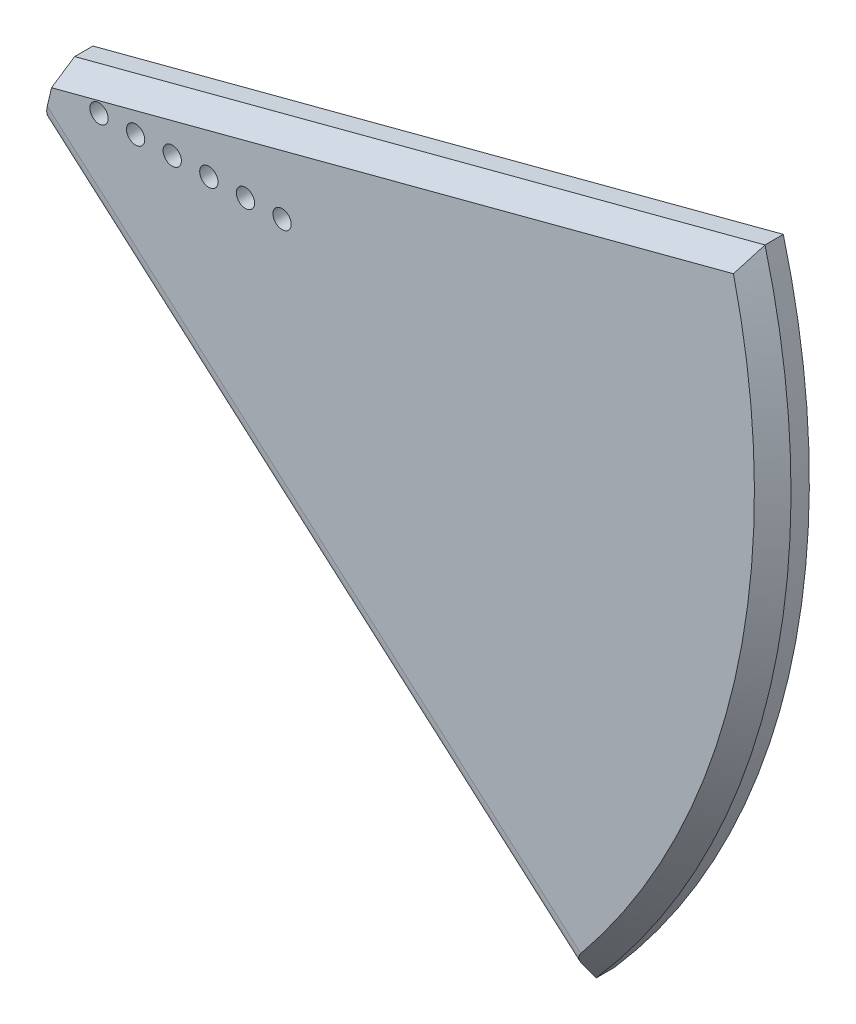
SolidWorks part; units mm, degrees
ref_plane "Front Plane" through (0, 0, 0) normal (0, 0, 1) x (1, 0, 0)
ref_plane "Top Plane" through (0, 0, 0) normal (0, 1, 0) x (1, 0, 0)
ref_plane "Right Plane" through (0, 0, 0) normal (1, 0, 0) x (0, 0, -1)
sketch "Sketch1" plane through (0, 0, 0) normal (0, 0, 1) x (1, 0, 0)
  line L0 (0, 0) -> (6.2, 0) construction
  line L2 (3.0097, -2.6348) -> (32.3538, -28.3237) construction
  line L11 (6.2, 0) -> (8.2, 0) construction
  line L12 (8.2, 0) -> (10.2, 0) construction
  line L15 (10.2, 0) -> (12.2, 0) construction
  line L16 (12.2, 0) -> (14.2, 0) construction
  line L17 (14.2, 0) -> (16.2, 0) construction
  line L18 (6.2, 0) -> (8.2, 0) construction
  line L20 (8.2, 0) -> (10.2, 0) construction
  line L21 (10.2, 0) -> (12.2, 0) construction
  line L22 (12.2, 0) -> (14.2, 0) construction
  line L23 (14.2, 0) -> (16.2, 0) construction
  line L24 (16.2, 0) -> (35, 0) construction
  line L27 (0, 0) -> (26.3345, -23.0542) construction
  line L28 (0, 0) -> (33.8429, 8.9253) construction
  line L29 (3.8678, 1.02) -> (41.5784, 10.9654) construction
  line L36 (3.8678, 1.02) -> (41.5784, 10.9654)
  line L37 (3.0097, -2.6348) -> (32.3538, -28.3237)
  line L38 (3.0097, -2.6348) -> (3.8678, 1.02)
  circle A1 centre (35, 0) radius 7 construction
  circle A6 centre (0, 0) radius 35 construction
  circle A8 centre (0, 0) radius 43 construction
  circle A9 centre (31.3429, -15.5764) radius 7 construction
  circle A24 centre (6.2, 0) radius 0.5
  circle A25 centre (8.2, 0) radius 0.5
  circle A26 centre (10.2, 0) radius 0.5
  circle A27 centre (12.2, 0) radius 0.5
  circle A28 centre (14.2, 0) radius 0.5
  circle A29 centre (16.2, 0) radius 0.5
  circle A31 centre (0, 0) radius 4 construction
  arc A32 (3.0097, -2.6348) -> (3.8678, 1.02) centre (0, 0) ccw construction
  arc A33 (32.3538, -28.3237) -> (41.5784, 10.9654) centre (0, 0) ccw construction
  arc A34 (41.5784, 10.9654) -> (32.3538, -28.3237) centre (0, 0) cw
  point P1 (3.8678, 1.02)
  point P6 (3.0097, -2.6348)
  dimension "D3" = 1
  dimension "D5" = 70
  dimension "D6" = 86
  dimension "D8" = 14
  dimension "D11" = 14
  dimension "D12" = 8
  dimension "D2" = 2
  dimension "D4" = 6.2
  dimension "D9" = 16
  dimension "D7" = 9
  dimension "D10" = 9
extrude "Boss-Extrude1" add sketch "Sketch1" along normal blind 2
chamfer "Chamfer1" distance 1 angle 45 3 edges at (22.7231, 5.9927, 2) (17.6817, -15.4792, 2) (41.8617, -9.8286, 2)
fillet "Fillet1" radius 1 1 edges at (17.7598, -14.2185, 2)
equation "\"InnerTubeDiameterServoGate\"=14"
equation "\"ServoGateDiameter\"=70"
equation "\"D5@Sketch1\"=\"ServoGateDiameter\""
equation "\"D6@Sketch1\"=\"ServoGateDiameter\"+\"InnerTubeDiameterServoGate\"+2mm"
equation "\"D8@Sketch1\"=\"InnerTubeDiameterServoGate\""
equation "\"D9@Sketch1\"=\"InnerTubeDiameterServoGate\"+2mm"
equation "\"D11@Sketch1\"=\"InnerTubeDiameterServoGate\""
equation "\"D7@Sketch1\"=\"InnerTubeDiameterServoGate\"/2+2mm"
equation "\"D10@Sketch1\"=\"InnerTubeDiameterServoGate\"/2+2mm"
